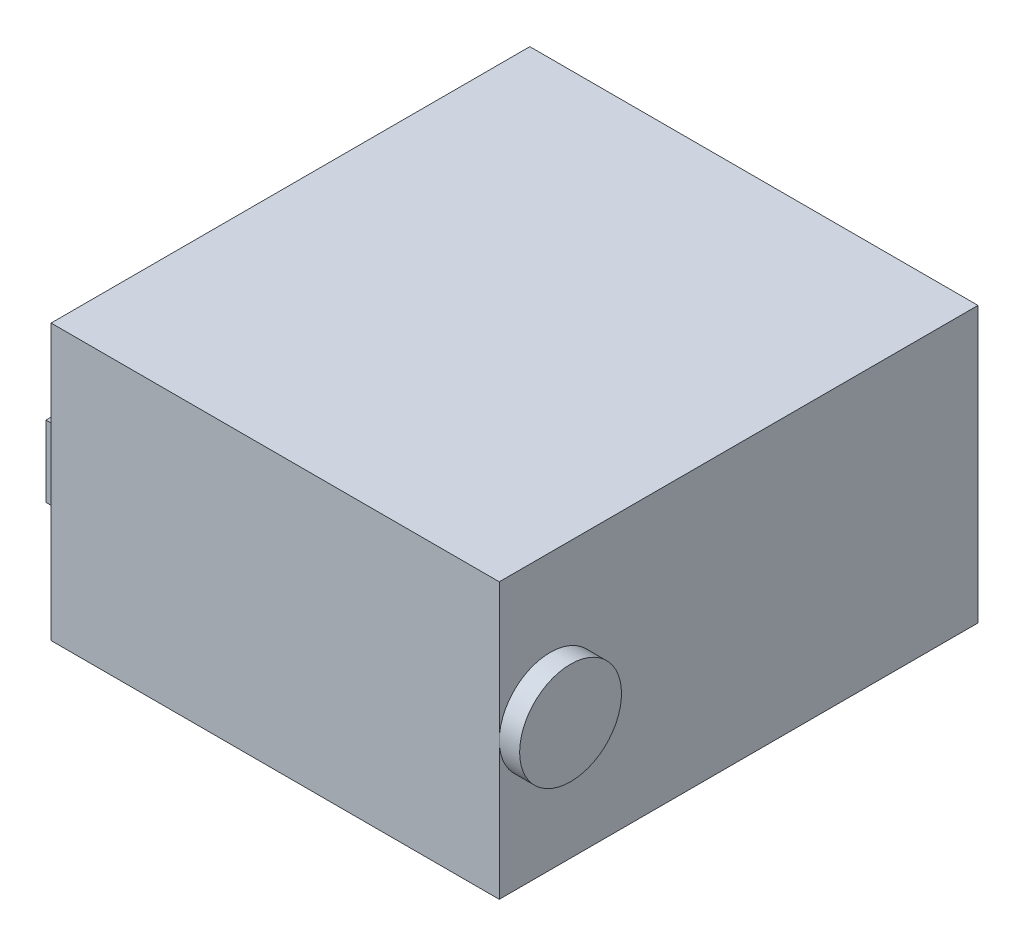
SolidWorks part; units mm, degrees
ref_plane "Front Plane" through (0, 0, 0) normal (0, 0, 1) x (1, 0, 0)
ref_plane "Top Plane" through (0, 0, 0) normal (0, 1, 0) x (1, 0, 0)
ref_plane "Right Plane" through (0, 0, 0) normal (1, 0, 0) x (0, 0, -1)
sketch "Sketch1" plane through (0, 0, 0) normal (0, 1, 0) x (1, 0, 0)
  line L1 (0, 0) -> (139.7, 0)
  line L2 (0, 0) -> (0, 149.225)
  line L3 (0, 149.225) -> (139.7, 149.225)
  line L4 (139.7, 0) -> (139.7, 149.225)
  dimension "D1" = 149.225
  dimension "D2" = 139.7
extrude "Boss-Extrude1" add sketch "Sketch1" along normal blind 85.725
sketch "Sketch2" plane through (0, 0, 0) normal (-1, 0, 0) x (0, 0, 1)
  line L0 (0, 85.725) -> (0, 0) construction
  line L1 (-53.975, 53.975) -> (-4.7625, 53.975)
  line L2 (-53.975, 53.975) -> (-53.975, 31.75)
  line L3 (-53.975, 31.75) -> (-4.7625, 31.75)
  line L4 (-4.7625, 53.975) -> (-4.7625, 31.75)
  point P6 (-4.7625, 42.8625)
  dimension "D1" = 4.7625
  dimension "D2" = 53.975
  dimension "D3" = 22.225
  dimension "D4" = 42.8625
extrude "Boss-Extrude2" add sketch "Sketch2" along normal blind 6.35
sketch "Sketch3" plane through (139.7, 0, 0) normal (1, 0, 0) x (0, 0, -1)
  line L0 (0, 85.725) -> (0, 0) construction
  circle A0 centre (15.875, 42.8625) radius 15.875
  point P4 (0, 0)
  point P5 (15.875, 28.3919)
  point P6 (0, 42.8625)
  dimension "D1" = 31.75
extrude "Boss-Extrude3" add sketch "Sketch3" along normal blind 6.35
equation "\"D4@Sketch2\"=(3+3/8)/2"
